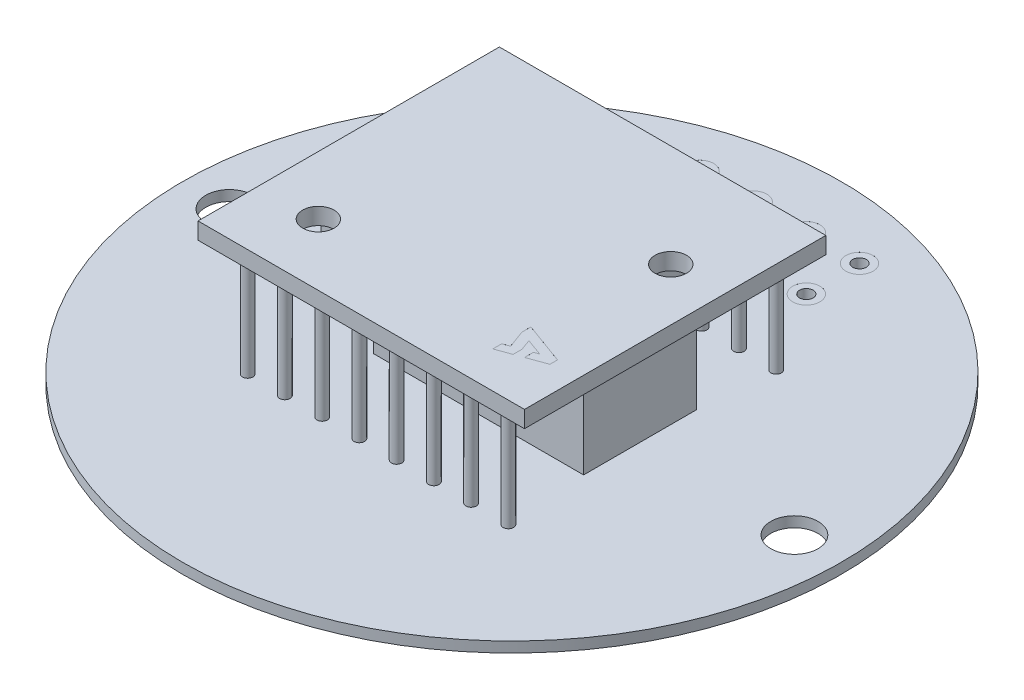
SolidWorks part; units mm, degrees
ref_plane "Front Plane" through (0, 0, 0) normal (0, 0, 1) x (1, 0, 0)
ref_plane "Top Plane" through (0, 0, 0) normal (0, 1, 0) x (1, 0, 0)
ref_plane "Right Plane" through (0, 0, 0) normal (1, 0, 0) x (0, 0, -1)
sketch "Sketch1" plane through (0, 0, 0) normal (0, 1, 0) x (1, 0, 0)
  circle A0 centre (0, 0) radius 15.75
  dimension "D1" = 31.5
extrude "Boss-Extrude1" add sketch "Sketch1" along normal blind 0.5
sketch "Sketch2" plane through (0, 0.5, 0) normal (0, 1, 0) x (1, 0, 0)
  line L1 (-7.8, -7.2) -> (7.8, -7.2)
  line L2 (-7.8, -7.2) -> (-7.8, 7.2)
  line L3 (-7.8, 7.2) -> (7.8, 7.2)
  line L4 (7.8, -7.2) -> (7.8, 7.2)
  line L5 (-7.8, -7.2) -> (7.8, 7.2) construction
  line L6 (-7.8, 7.2) -> (7.8, -7.2) construction
  circle A0 centre (-5, -4.25) radius 0.75
  circle A1 centre (5.29, 2.3) radius 0.75
  point P0 (0, 0)
  dimension "D7" = 1.5
  dimension "D1" = 15.6
  dimension "D2" = 14.4
  dimension "D3" = 10.29
  dimension "D4" = 6.55
  dimension "D5" = 2.95
  dimension "D6" = 2.8
extrude "Boss-Extrude2" add sketch "Sketch2" along normal blind 0.8 from offset 5.15 separate body
sketch "Sketch3" plane through (0, 6.45, 0) normal (0, 1, 0) x (1, 0, 0)
  line L0 (6.54, -4.3622) -> (4.54, -3.6343)
  line L1 (4.54, -3.6343) -> (4.54, -4.0599)
  line L2 (4.54, -4.0599) -> (4.8513, -4.9152)
  line L3 (4.8513, -4.9152) -> (4.54, -5.0285)
  line L4 (4.54, -5.0285) -> (4.54, -5.4541)
  line L5 (4.54, -5.4541) -> (5.2513, -5.1952)
  line L7 (5.8705, -4.5442) -> (5.0622, -4.25)
  line L9 (5.8705, -4.5442) -> (5.6513, -4.624)
  line L10 (5.6513, -4.624) -> (5.6513, -5.0497)
  line L11 (5.6513, -5.0497) -> (6.54, -4.7262)
  line L12 (5.2513, -5.1952) -> (5.2513, -4.7696)
  line L13 (5.2513, -4.7696) -> (5.0622, -4.25)
  line L14 (5.2513, -4.3188) -> (5.2513, -3.8932) construction
  line L15 (4.54, -3.6343) -> (7.04, -3.6343) construction
  line L16 (7.04, -3.6343) -> (7.04, -5.4541) construction
  line L17 (7.04, -5.4541) -> (4.54, -5.4541) construction
  line L18 (-5, -4.25) -> (5.0622, -4.25) construction
  line L19 (5.2513, -4.7696) -> (5.6513, -4.624) construction
  line L20 (4.8513, -4.9152) -> (5.2513, -4.7696) construction
  line L21 (4.54, 2.3) -> (4.54, -3.6343) construction
  line L22 (6.54, -4.3622) -> (6.54, -4.7262)
  line L23 (7.04, -4.5442) -> (6.54, -4.3622) construction
  line L24 (6.54, -4.7262) -> (7.04, -4.5442) construction
  circle A0 centre (5.29, 2.3) radius 0.75 construction
  dimension "D1" = 40
  dimension "D2" = 2.5
  dimension "D3" = 0.4
  dimension "D4" = 2
extrude "Cut-Extrude1" cut sketch "Sketch3" against normal blind 0.001
sketch "Sketch4" plane through (0, 5.65, 0) normal (0, -1, 0) x (1, 0, 0)
  line L0 (7.8, -7.2) -> (-7.8, -7.2) construction
  line L1 (7.425, 4) -> (-7.425, 4)
  line L2 (7.425, 4) -> (7.425, -4)
  line L3 (7.425, -4) -> (-7.425, -4)
  line L4 (-7.425, 4) -> (-7.425, -4)
  line L5 (7.425, 4) -> (-7.425, -4) construction
  line L6 (7.425, -4) -> (-7.425, 4) construction
  line L7 (7.8, 4) -> (7.425, 4) construction
  line L8 (7.8, 7.2) -> (7.8, -7.2) construction
  line L9 (-7.425, 4) -> (-7.8, 4) construction
  line L10 (-7.8, -7.2) -> (-7.8, 7.2) construction
  line L11 (-7.425, 1.7) -> (-3.625, 1.7)
  line L12 (-2.625, 2.7) -> (-2.625, 4)
  line L13 (7.425, -1.4) -> (5.425, -1.4)
  line L14 (4.425, -2.4) -> (4.425, -4)
  arc A0 (-3.625, 1.7) -> (-2.625, 2.7) centre (-3.625, 2.7) ccw
  arc A1 (5.425, -1.4) -> (4.425, -2.4) centre (5.425, -2.4) ccw
  point P0 (0, 0)
  point P23 (4.425, -1.4)
  circle M15 centre (5.29, -2.3) radius 0.75
  dimension "D8" = 1
  dimension "D1" = 8
  dimension "D2" = 14.85
  dimension "D3" = 7.2
  dimension "D4" = 2.3
  dimension "D5" = 4.8
  dimension "D6" = 2.6
  dimension "D7" = 3
extrude "Boss-Extrude3" add sketch "Sketch4" along normal blind 3.7 contours L14 L13 L2 L1 L12 L11 L4 L3 M15
sketch "Sketch5" plane through (0, 5.65, 0) normal (0, -1, 0) x (1, 0, 0)
  line L0 (7.8, 7.2) -> (7.8, -7.2) construction
  line L1 (7.8, -7.2) -> (-7.8, -7.2) construction
  line L2 (6.23, 6.4) -> (6.23, -6.4) construction
  line L3 (6.23, -6.4) -> (6.23, -7.2) construction
  line L4 (6.23, 6.4) -> (6.23, 7.2) construction
  line L5 (-7.8, 7.2) -> (7.8, 7.2) construction
  circle A0 centre (6.23, 6.4) radius 0.25
  circle A1 centre (6.23, -6.4) radius 0.25
  circle A2 centre (4.45, 6.4) radius 0.25
  circle A3 centre (4.45, -6.4) radius 0.25
  circle A4 centre (2.67, 6.4) radius 0.25
  circle A5 centre (2.67, -6.4) radius 0.25
  circle A6 centre (0.89, 6.4) radius 0.25
  circle A7 centre (0.89, -6.4) radius 0.25
  circle A8 centre (-0.89, 6.4) radius 0.25
  circle A9 centre (-0.89, -6.4) radius 0.25
  circle A10 centre (-2.67, 6.4) radius 0.25
  circle A11 centre (-2.67, -6.4) radius 0.25
  circle A12 centre (-4.45, 6.4) radius 0.25
  circle A13 centre (-4.45, -6.4) radius 0.25
  circle A14 centre (-6.23, 6.4) radius 0.25
  circle A15 centre (-6.23, -6.4) radius 0.25
  dimension "D3" = 0.5
  dimension "D1" = 1.57
  dimension "D2" = 0.8
  dimension "D4" = 8
extrude "Boss-Extrude4" add sketch "Sketch5" along normal up to next
hole_wizard "#2 Clearance Hole1" positions "Sketch7" profile "Sketch9" hole size "#2" standard "ANSI Inch" end condition up to next
sketch "Sketch7" plane through (0, 0.5, 0) normal (0, 1, 0) x (1, 0, 0)
  line L0 (13.5, 0) -> (0, 0) construction
  line L1 (0, 0) -> (-13.5, 0) construction
  point P0 (13.5, 0)
  point P2 (-13.5, 0)
  dimension "D1" = 27
sketch "Sketch9" plane through (13.5, 0.5, 0) normal (1, 0, 0) x (0, 0, 1)
  line L0 (0, 0) -> (0, 0.5)
  line L1 (0, 0.5) -> (1.13, 0.5)
  line L2 (1.13, 0.5) -> (1.13, 0)
  line L5 (1.13, 0) -> (0, 0)
  line L11 (0, -6.35) -> (0, 107.95) construction
  dimension "Thru Hole Dia." = 2.26
  dimension "Thru Hole Depth" = 0.5
sketch "Sketch10" plane through (0, 0.5, 0) normal (0, 1, 0) x (1, 0, 0)
  line L0 (0, 0) -> (3.81, 0) construction
  line L1 (3.81, 0) -> (3.81, 12.8) construction
  line L2 (0, 0) -> (-3.81, 0) construction
  line L3 (3.81, 12.8) -> (-3.81, 12.8) construction
  line L4 (3.81, 12.8) -> (3.81, 10.26) construction
  line L5 (3.81, 10.26) -> (-3.81, 10.26) construction
  line L6 (-3.81, 12.8) -> (-3.81, 10.26) construction
  line L7 (3.81, 12.8) -> (-3.81, 10.26) construction
  line L8 (3.81, 10.26) -> (-3.81, 12.8) construction
  line L9 (-3.81, 0) -> (-3.81, 10.26) construction
  circle A0 centre (3.81, 12.8) radius 0.325
  circle A1 centre (1.27, 12.8) radius 0.325
  circle A2 centre (-1.27, 12.8) radius 0.325
  circle A3 centre (-3.81, 12.8) radius 0.325
  circle A4 centre (1.27, 10.26) radius 0.325
  circle A5 centre (-1.27, 10.26) radius 0.325
  circle A6 centre (-3.81, 10.26) radius 0.325
  circle A7 centre (3.81, 10.26) radius 0.325
  point P6 (0, 11.53)
  dimension "D1" = 0.65
  dimension "D4" = 2.54
  dimension "D5" = 2.54
  dimension "D6" = 12.8
  dimension "D2" = 4
  dimension "D3" = 2
extrude "Cut-Extrude2" cut sketch "Sketch10" against normal through all
sketch "Sketch11" plane through (0, 0.5, 0) normal (0, 1, 0) x (1, 0, 0)
  circle A0 centre (3.81, 12.8) radius 0.65
  circle A1 centre (1.27, 12.8) radius 0.65
  circle A2 centre (-1.27, 12.8) radius 0.65
  circle A3 centre (-3.81, 12.8) radius 0.65
  circle A4 centre (1.27, 10.26) radius 0.65
  circle A5 centre (-1.27, 10.26) radius 0.65
  circle A6 centre (-3.81, 10.26) radius 0.65
  circle A7 centre (3.81, 10.26) radius 0.65
  point P3 (3.81, 10.2434)
  point P4 (-3.81, 12.8)
  point P5 (-3.81, 10.26)
  dimension "D1" = 1.3
  dimension "D2" = 4
  dimension "D3" = 2
extrude "Cut-Extrude3" cut sketch "Sketch11" against normal blind 0.001
